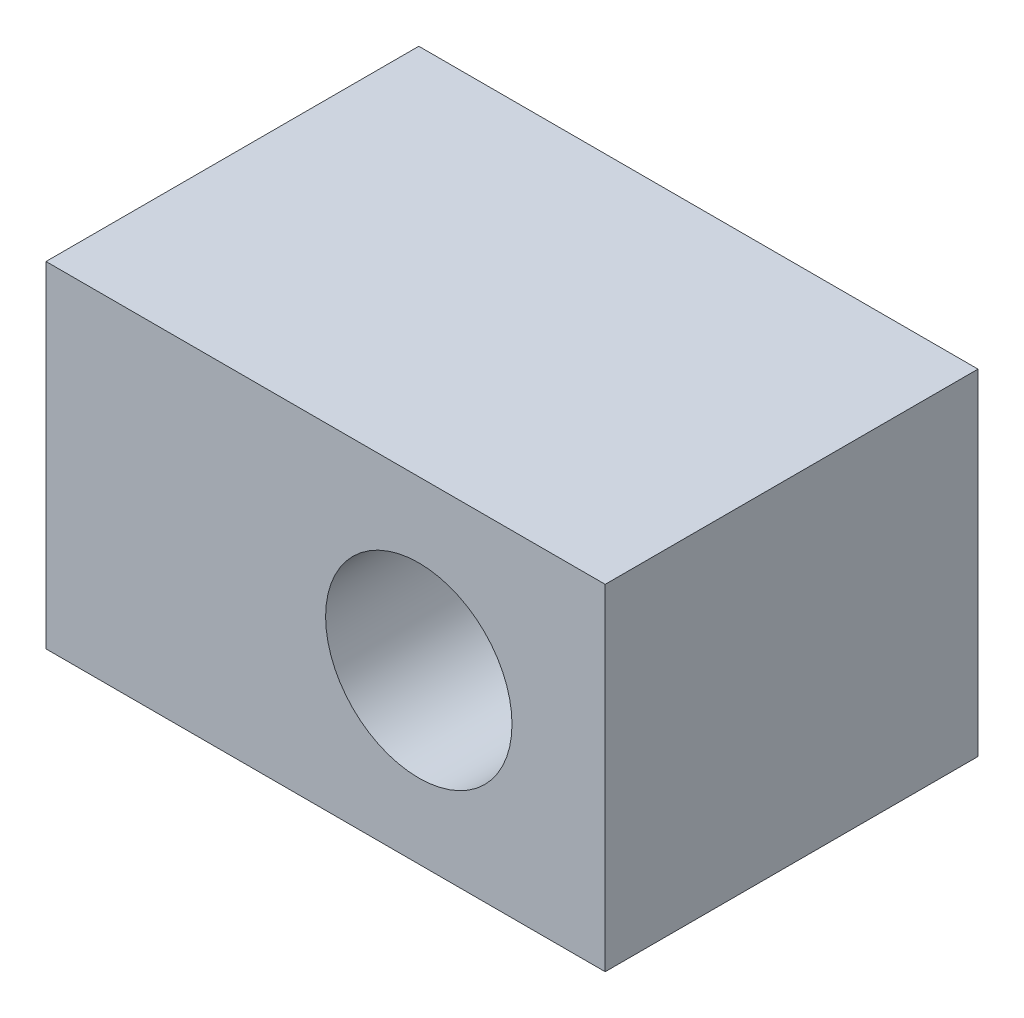
SolidWorks part; units mm, degrees
material "6061-T6 (SS)"
ref_plane "Front Plane" through (0, 0, 0) normal (0, 0, 1) x (1, 0, 0)
ref_plane "Top Plane" through (0, 0, 0) normal (0, 1, 0) x (1, 0, 0)
ref_plane "Right Plane" through (0, 0, 0) normal (1, 0, 0) x (0, 0, -1)
sketch "Sketch1" plane through (0, 0, 0) normal (0, 0, 1) x (1, 0, 0)
  line L4 (-9.525, -5.715) -> (9.525, -5.715)
  line L5 (-9.525, -5.715) -> (-9.525, 5.715)
  line L6 (-9.525, 5.715) -> (9.525, 5.715)
  line L7 (9.525, -5.715) -> (9.525, 5.715)
  line L8 (-9.525, -5.715) -> (9.525, 5.715) construction
  line L9 (-9.525, 5.715) -> (9.525, -5.715) construction
  point P0 (0, 0)
  dimension "D1" = 11.43
  dimension "D2" = 19.05
extrude "Boss-Extrude1" add sketch "Sketch1" along normal blind 12.7
sketch "Sketch3" plane through (0, 0, 12.7) normal (0, 0, 1) x (1, 0, 0)
  line L0 (9.525, -5.715) -> (9.525, 5.715) construction
  circle A0 centre (3.175, 0) radius 3.175
  point P4 (0, 0)
  point P5 (0, 0)
  point P6 (0, -1.9)
  point P8 (0, 0)
  dimension "D1" = 6.35
  dimension "D2" = 6.35
extrude "Cut-Extrude1" cut sketch "Sketch3" against normal through all
sketch "Sketch8" plane through (-9.525, 0, 0) normal (-1, 0, 0) x (0, 0, 1)
  line L0 (0, 5.715) -> (0, -5.715) construction
  line L3 (12.7, 5.715) -> (0, 5.715) construction
  circle A0 centre (6.35, 0) radius 2.4892
  point P4 (0, 0)
  point P7 (6.35, 5.715)
  dimension "D1" = 4.9784
hole_wizard "#10-32 Tapped Hole3" positions "3DSketch6" profile "Sketch13" tap size "#10-32" standard "ANSI Inch"
sketch3d "3DSketch6"
  point P0 (-9.525, 0, 6.35)
sketch "Sketch13" plane through (-9.525, 0, 6.35) normal (0, 1, 0) x (0, 0, 1)
  line L0 (0, 0) -> (0, 8.6708)
  line L1 (0, 8.6708) -> (2.0193, 7.4574)
  line L2 (2.0193, 7.4574) -> (2.0193, 0)
  line L5 (2.0193, 0) -> (0, 0)
  line L10 (0, 8.6708) -> (-2.0193, 7.4574) construction
  line L11 (0, -6.35) -> (0, 107.95) construction
  dimension "Tap Drill Dia." = 4.0386
  dimension "Tap Drill Depth" = 7.4574
  dimension "Drill Angle" = 118
cosmetic thread "Hole Thread5"
